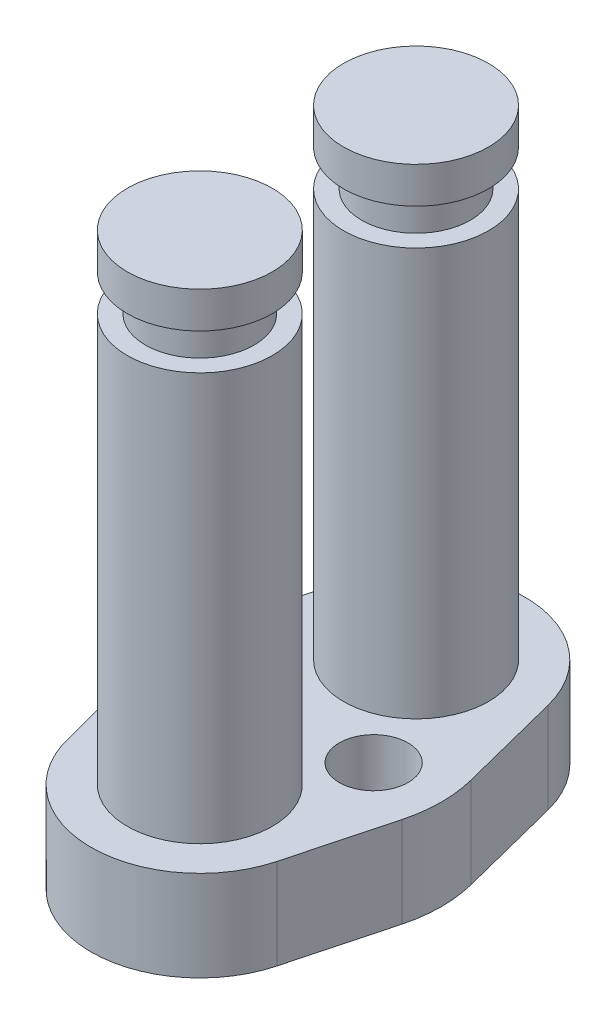
SolidWorks part; units mm, degrees
ref_plane "Front Plane" through (0, 0, 0) normal (0, 0, 1) x (1, 0, 0)
ref_plane "Top Plane" through (0, 0, 0) normal (0, 1, 0) x (1, 0, 0)
ref_plane "Right Plane" through (0, 0, 0) normal (1, 0, 0) x (0, 0, -1)
sketch "Sketch2" plane through (0, 0, 0) normal (0, 1, 0) x (1, 0, 0)
  line L0 (3.75, 7.5) -> (3.75, -7.5) construction
  line L1 (-3.4934, -1.9449) -> (-1.9217, -7.7985)
  line L2 (10.9985, -1.9261) -> (9.5488, -7.3818)
  line L3 (11.0189, 1.8474) -> (9.5651, 7.5676)
  line L4 (-2.0651, 7.5676) -> (-3.5189, 1.8474)
  circle A0 centre (7.5, 0) radius 2.5 construction
  circle A1 centre (0, 0) radius 2.5 construction
  circle A2 centre (3.75, 0) radius 7.5
  circle A3 centre (3.75, 6.0897) radius 4 construction
  circle A4 centre (3.75, -5.841) radius 4 construction
  circle A5 centre (3.75, 6.0897) radius 6
  circle A6 centre (3.75, -5.841) radius 6
  dimension "D1" = 7.5
  dimension "D2" = 5
  dimension "D4" = 15
  dimension "D5" = 12
  dimension "D6" = 12
  dimension "D7" = 8
  dimension "D8" = 8
  dimension "D3" = 3.75
extrude "Boss-Extrude2" add sketch "Sketch2" along normal blind 5 contours A2 A6 A0 A5 A1 | A6 A2 L1 | A6 A2 A5 A0 | A6 L2 A2 | A6 A1 A5 A2 | A6 A2 L1 | A6 A0 A5 | A5 A6 | A6 A5 A1 | A6 A5 A0 A2 A1 | A2 A5 | A5 A2 L3 | A5 L4 A2
sketch "Sketch3" plane through (0, 5, 0) normal (0, 1, 0) x (1, 0, 0)
  line L0 (3.75, -11.841) -> (3.75, 12.0897) construction
  line L1 (-3.7498, -0.0504) -> (11.2499, -0.0406) construction
  circle A0 centre (3.75, -5.841) radius 4
  circle A1 centre (3.75, 6.0897) radius 4
  arc A2 (-1.9217, -7.7985) -> (9.5488, -7.3818) centre (3.75, -5.841) ccw construction
  arc A3 (9.5651, 7.5676) -> (-2.0651, 7.5676) centre (3.75, 6.0897) ccw construction
  arc A4 (-3.5189, 1.8474) -> (-3.4934, -1.9449) centre (3.75, 0) ccw construction
  arc A5 (10.9985, -1.9261) -> (11.0189, 1.8474) centre (3.75, 0) ccw construction
  dimension "D1" = 8
extrude "Boss-Extrude3" add sketch "Sketch3" along normal blind 22.5
sketch "Sketch4" plane through (0, 27.5, 0) normal (0, 1, 0) x (1, 0, 0)
  circle A0 centre (3.75, -5.841) radius 3
  circle A1 centre (3.75, 6.0897) radius 3
  circle A2 centre (3.75, -5.841) radius 4 construction
  circle A3 centre (3.75, 6.0897) radius 4 construction
  dimension "D1" = 6
  dimension "D2" = 6
extrude "Boss-Extrude4" add sketch "Sketch4" along normal blind 2
sketch "Sketch5" plane through (0, 29.5, 0) normal (0, 1, 0) x (1, 0, 0)
  circle A0 centre (3.75, -5.841) radius 4
  circle A1 centre (3.75, 6.0897) radius 4
  dimension "D1" = 8
  dimension "D2" = 8
extrude "Boss-Extrude5" add sketch "Sketch5" along normal blind 2
hole_wizard "#6 Clearance Hole1" positions "Sketch6" profile "Sketch7" hole size "#6" standard "ANSI Inch" end condition through all
sketch "Sketch6" plane through (0, 5, 0) normal (0, 1, 0) x (1, 0, 0)
  point P0 (0, 0)
  point P3 (7.5, 0)
sketch "Sketch7" plane through (0, 5, 0) normal (1, 0, 0) x (0, 0, 1)
  line L0 (0, 0) -> (0, 5)
  line L1 (0, 5) -> (1.8986, 5)
  line L2 (1.8986, 5) -> (1.8986, 0)
  line L5 (1.8986, 0) -> (0, 0)
  line L11 (0, -6.35) -> (0, 107.95) construction
  dimension "Thru Hole Dia." = 3.7973
  dimension "Thru Hole Depth" = 5
